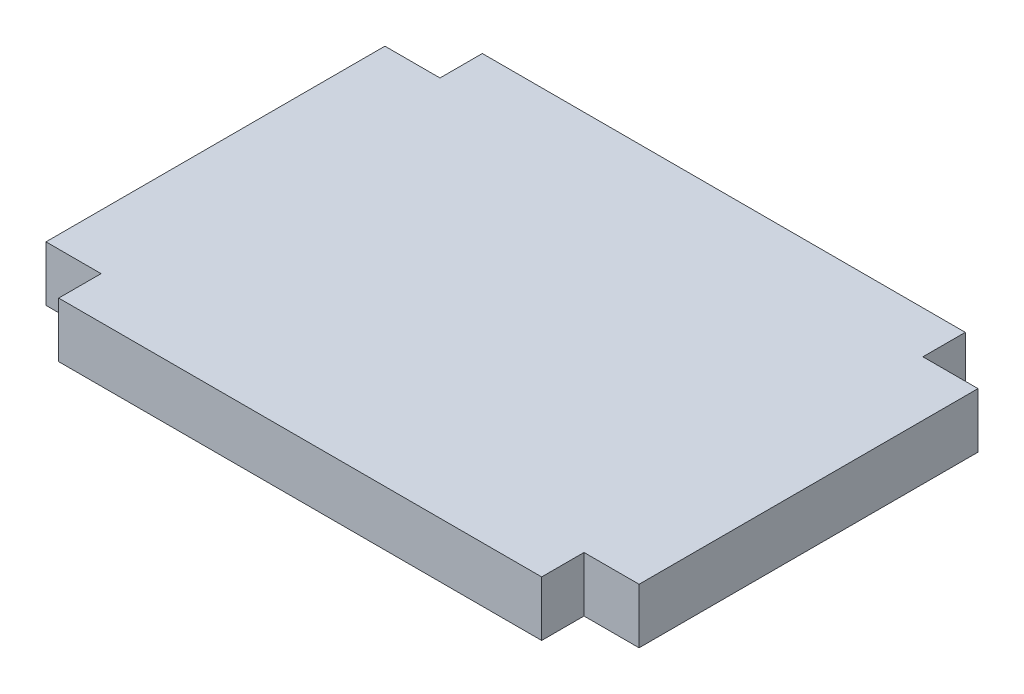
SolidWorks part; units mm, degrees
ref_plane "Front Plane" through (0, 0, 0) normal (0, 0, 1) x (1, 0, 0)
ref_plane "Top Plane" through (0, 0, 0) normal (0, 1, 0) x (1, 0, 0)
ref_plane "Right Plane" through (0, 0, 0) normal (1, 0, 0) x (0, 0, -1)
sketch "Sketch1" plane through (0, 0, 0) normal (0, 1, 0) x (1, 0, 0)
  line L1 (-5.7, 5) -> (5.7, 5)
  line L2 (-5.7, 5) -> (-5.7, -5)
  line L3 (-5.7, -5) -> (5.7, -5)
  line L4 (5.7, 5) -> (5.7, -5)
  line L5 (-5.7, 5) -> (5.7, -5) construction
  line L6 (-5.7, -5) -> (5.7, 5) construction
  point P0 (0, 0)
  dimension "D1" = 10
  dimension "D2" = 11.4
extrude "Boss-Extrude1" add sketch "Sketch1" along normal blind 1.3
sketch "Sketch2" plane through (0, 1.3, 0) normal (0, 1, 0) x (1, 0, 0)
  line L0 (-5.7, 5) -> (-5.7, -5) construction
  line L1 (-5.7, 4) -> (-7, 4)
  line L2 (-5.7, 4) -> (-5.7, -4)
  line L3 (-5.7, -4) -> (-7, -4)
  line L4 (-7, 4) -> (-7, -4)
  line L5 (5.7, -5) -> (5.7, 5) construction
  line L6 (5.7, 4) -> (7, 4)
  line L7 (5.7, 4) -> (5.7, -4)
  line L8 (5.7, -4) -> (7, -4)
  line L9 (7, 4) -> (7, -4)
  line L10 (-55, 0) -> (55, 0) construction
  dimension "D1" = 1.3
  dimension "D2" = 1.3
  dimension "D3" = 8
  dimension "D4" = 8
  dimension "D5" = 4
  dimension "D6" = 4
extrude "Boss-Extrude2" add sketch "Sketch2" against normal blind 1.3
